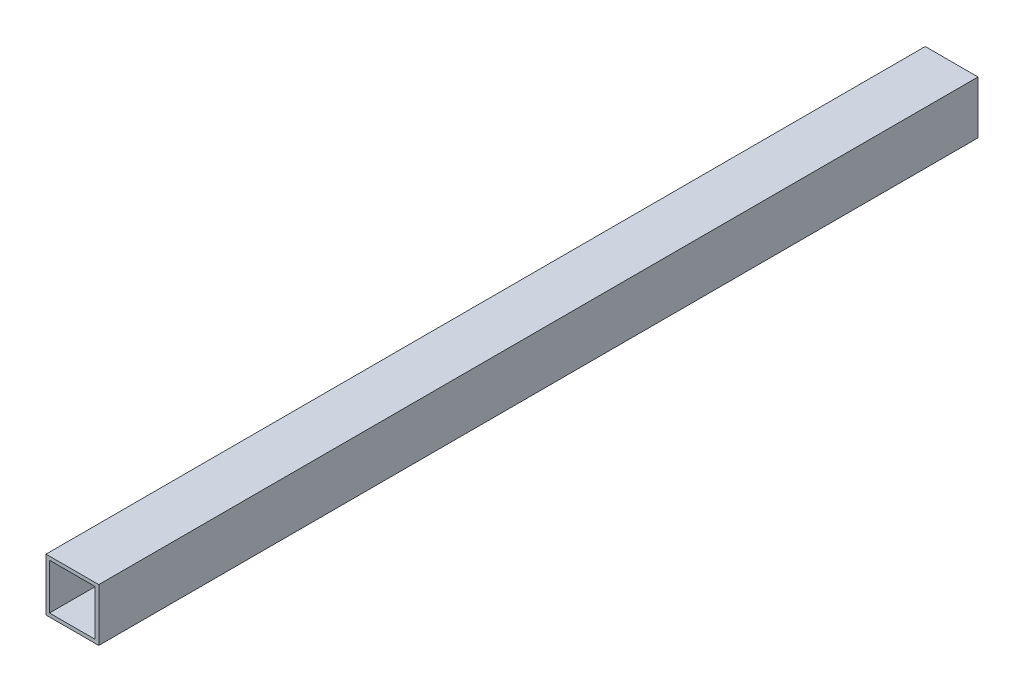
SolidWorks part; units mm, degrees
material "Aleación 1060"
ref_plane "Alzado" through (0, 0, 0) normal (0, 0, 1) x (1, 0, 0)
ref_plane "Planta" through (0, 0, 0) normal (0, 1, 0) x (1, 0, 0)
ref_plane "Vista lateral" through (0, 0, 0) normal (1, 0, 0) x (0, 0, -1)
sketch "Croquis1" plane through (0, 0, 0) normal (0, 0, 1) x (1, 0, 0)
  line L1 (15, -15) -> (-15, -15)
  line L2 (15, -15) -> (15, 15)
  line L3 (15, 15) -> (-15, 15)
  line L4 (-15, -15) -> (-15, 15)
  line L5 (15, -15) -> (-15, 15) construction
  line L6 (15, 15) -> (-15, -15) construction
  point P0 (0, 0)
  dimension "D1" = 30
  dimension "D2" = 30
extrude "Extruir-Lámina1" add sketch "Croquis1" along normal blind 500 thin
